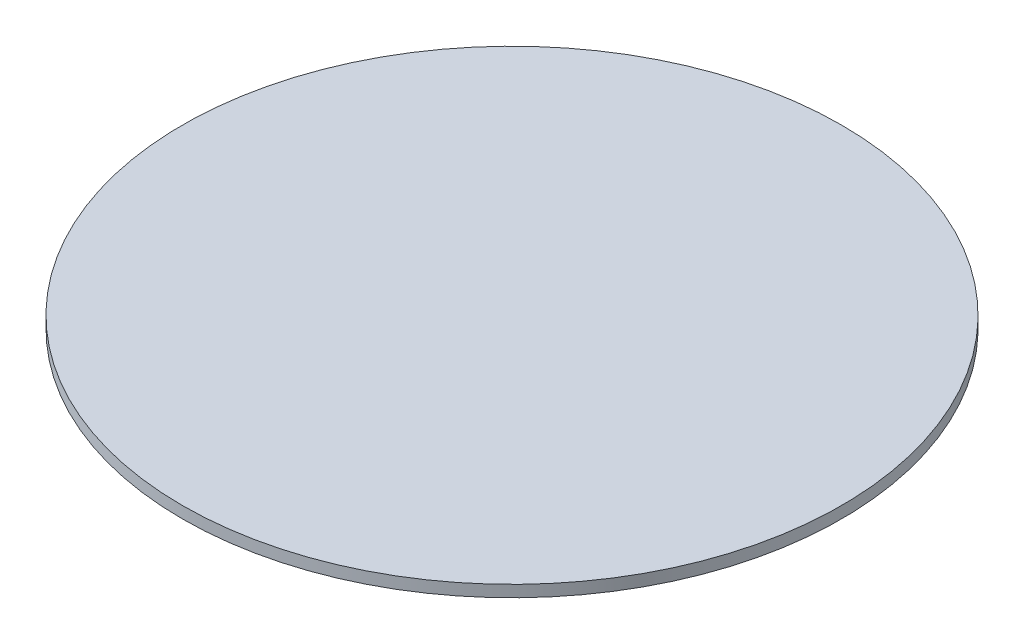
SolidWorks part; units mm, degrees
material "Balsa"
ref_plane "Front Plane" through (0, 0, 0) normal (0, 0, 1) x (1, 0, 0)
ref_plane "Top Plane" through (0, 0, 0) normal (0, 1, 0) x (1, 0, 0)
ref_plane "Right Plane" through (0, 0, 0) normal (1, 0, 0) x (0, 0, -1)
sketch "Sketch1" plane through (0, 0, 0) normal (0, 1, 0) x (1, 0, 0)
  circle A0 centre (0, 0) radius 85
  dimension "D1" = 85
extrude "Boss-Extrude1" add sketch "Sketch1" along normal blind 3 contours A0
equation "\"Ring inner radius\"= 80mm"
equation "\"D1@Sketch1\"=\"Ring inner radius\" + \"Plexiglass step\""
equation "\"Heart cable hole radius\"= 3.5mm"
equation "\"Dogbone radius\"= 3mm"
equation "\"Tree side stock thickness\"= 6.7mm"
equation "\"Ring stock thickness\"= 6.7mm"
equation "\"D1@Boss-Extrude1\"=\"Plexiglass thickness\""
equation "\"Tree teeth\"= 15mm"
equation "\"Tree slot\"= 15mm"
equation "\"Bottom ring outer radius\"= \"Ring inner radius\" + \"Tree teeth\""
equation "\"Cut-Extrude Tolerance\"= 5mm"
equation "\"Ring outer radius\"= \"Ring inner radius\" + \"Tree slot\" + 10"
equation "\"Plexiglass step\"= 5mm"
equation "\"Plexiglass thickness\"= 3mm"
